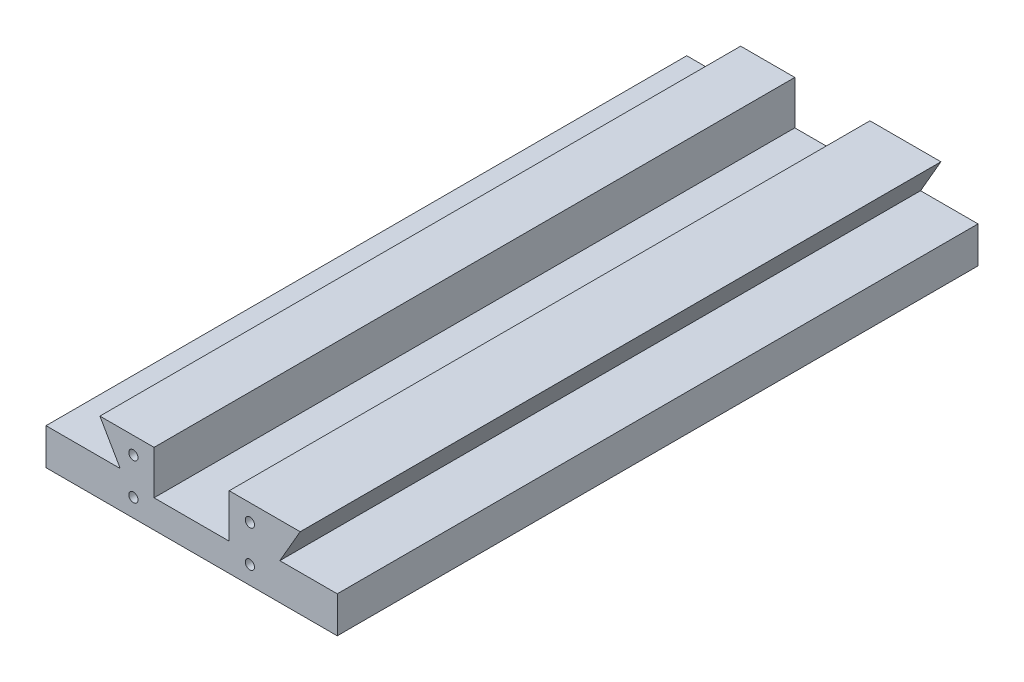
SolidWorks part; units mm, degrees
material "Ductile Iron"
ref_plane "Front Plane" through (0, 0, 0) normal (0, 0, 1) x (1, 0, 0)
ref_plane "Top Plane" through (0, 0, 0) normal (0, 1, 0) x (1, 0, 0)
ref_plane "Right Plane" through (0, 0, 0) normal (1, 0, 0) x (0, 0, -1)
sketch "Sketch6" plane through (0, 0, 0) normal (0, 0, 1) x (1, 0, 0)
  line B0 (-63.5, 0) -> (63.5, 0)
  line B1 (63.5, 0) -> (63.5, 15.875)
  line B2 (63.5, 15.875) -> (38.4596, 15.875)
  line B3 (38.4596, 15.875) -> (47.625, 31.75)
  line B4 (47.625, 31.75) -> (16.0563, 31.75)
  line B5 (-40.2927, 31.75) -> (-31.1272, 15.875)
  line B6 (-31.1272, 15.875) -> (-63.5, 15.875)
  line B7 (-63.5, 15.875) -> (-63.5, 0)
  line B8 (-38.4596, 15.875) -> (-47.625, 31.75)
  line B9 (-47.625, 31.75) -> (-40.2927, 31.75)
  line B10 (-16.0563, 31.75) -> (-16.0563, 12.7) construction
  line B11 (-16.0563, 12.7) -> (16.0563, 12.7) construction
  line B12 (16.0563, 12.7) -> (16.0563, 31.75) construction
  line B13 (-16.0563, 31.75) -> (-40.2927, 31.75)
  line B14 (-63.5, 15.875) -> (-63.5, 47.625)
  line B15 (-63.5, 47.625) -> (63.5, 47.625)
  line B16 (63.5, 47.625) -> (63.5, 15.875)
  line B17 (-16.0563, 31.75) -> (16.0563, 31.75) construction
  line B18 (0, 47.625) -> (0, 0) construction
  line B19 (-38.4596, 15.875) -> (38.4596, 15.875) construction
  line B20 (-28.702, 36.957) -> (28.702, 36.957) construction
  line B21 (-25.4, 7.874) -> (25.4, 7.874) construction
  line B22 (-25.4, 7.874) -> (-25.4, 23.8125) construction
  line B23 (25.4, 7.874) -> (25.4, 23.8125) construction
  line B24 (-52.832, 23.8125) -> (52.832, 23.8125) construction
  circle B25 centre (0, 22.225) radius 18.669 construction
  line B26 (40.2927, 31.75) -> (31.1272, 15.875)
  line B27 (31.1272, 15.875) -> (38.4596, 15.875)
  line B28 (-15.875, 31.75) -> (-15.875, 12.7)
  line B29 (-16.0563, 31.75) -> (-15.875, 31.75)
  line B30 (-15.875, 12.7) -> (15.875, 12.7)
  line B31 (15.875, 12.7) -> (15.875, 31.75)
  line B32 (15.875, 31.75) -> (16.0563, 31.75)
sketch_block_instance "dovetail pair-2"
sketch_block "dovetail pair" parameters "D8"=37.338, "D1"=60, "D2"=127, "D3"=6.35, "D4"=15.875, "D5"=31.75, "D6"=95.25, "D7"=19.05, "D9"=60, "D10"=31.75, "D11"=50.8, "D12"=23.876, "D13"=7.874, "D14"=10.668, "D15"=34.798, "D16"=21.082, "D17"=7.9375, "D18"=24.4437
sketch "dovetail-male-profile" plane through (0, 0, 0) normal (0, 0, 1) x (1, 0, 0)
  line L0 (47.3317, 31.242) -> (16.383, 31.242)
  line L1 (-16.383, 31.242) -> (-39.9994, 31.242)
  line L2 (16.383, 31.242) -> (16.383, 12.192)
  line L3 (16.383, 12.192) -> (-16.383, 12.192)
  line L4 (-16.383, 12.192) -> (-16.383, 31.242)
  line L5 (0, 47.625) -> (0, 0) construction
  line L7 (63.5, 15.875) -> (38.4596, 15.875) construction
  line L8 (63.5, 0) -> (63.5, 15.875) construction
  line L9 (-63.5, 0) -> (63.5, 0) construction
  line L10 (-63.5, 15.875) -> (-63.5, 0) construction
  line L11 (-31.1272, 15.875) -> (-63.5, 15.875) construction
  line L12 (38.4596, 15.875) -> (47.625, 31.75) construction
  line L13 (-31.1272, 15.875) -> (-39.9994, 31.242)
  line L15 (63.5, 15.875) -> (38.4596, 15.875)
  line L16 (63.5, 0) -> (63.5, 15.875)
  line L17 (-63.5, 0) -> (63.5, 0)
  line L18 (-63.5, 15.875) -> (-63.5, 0)
  line L19 (-31.1272, 15.875) -> (-63.5, 15.875)
  line L20 (-40.2927, 31.75) -> (-31.1272, 15.875) construction
  line L21 (38.4596, 15.875) -> (47.3317, 31.242)
  line L23 (47.625, 31.75) -> (16.0563, 31.75) construction
  line L25 (-16.0563, 12.7) -> (16.0563, 12.7) construction
  line L27 (15.875, 12.7) -> (15.875, 31.75) construction
  point P23 (0, 12.192)
  dimension "D2" = 0.508
  dimension "D1" = 0.508
  dimension "D3" = 0.508
extrude "x-guide-extrude" add sketch "dovetail-male-profile" along normal blind 279.4
hole_wizard "end plate holes" positions "Sketch2" profile "Sketch3" tap size "#10-32" standard "ANSI Inch"
sketch "Sketch2" plane through (0, 0, 0) normal (0, 0, -1) x (-1, 0, 0)
  point P27 (-25.4, 23.8125)
  point P29 (25.4, 23.8125)
  point P31 (25.4, 7.874)
  point P33 (-25.4, 7.874)
sketch "Sketch3" plane through (25.4, 23.8125, 0) normal (1, 0, 0) x (0, 1, 0)
  line L0 (0, 0) -> (0, 13.1513)
  line L1 (0, 13.1513) -> (2.0193, 11.938)
  line L2 (2.0193, 11.938) -> (2.0193, 0)
  line L3 (2.0193, 0) -> (0, 0)
  line L4 (0, 13.1513) -> (-2.0193, 11.938) construction
  line L5 (0, -6.35) -> (0, 107.95) construction
  dimension "Tap Drill Dia." = 4.0386
  dimension "Tap Drill Depth" = 11.938
  dimension "Drill Angle" = 118
cosmetic thread "Hole Thread1" parameters "D1"=9.652, "D2"=4.826
cosmetic thread "Hole Thread2" parameters "D1"=9.652, "D2"=4.826
cosmetic thread "Hole Thread9" parameters "D1"=9.652, "D2"=4.826
cosmetic thread "Hole Thread10" parameters "D1"=9.652, "D2"=4.826
hole_wizard "end plate holes 2" positions "Sketch4" profile "Sketch5" tap size "#10-32" standard "ANSI Inch"
sketch "Sketch4" plane through (0, 0, 279.4) normal (0, 0, 1) x (1, 0, 0)
  point P8 (25.4, 23.8125)
  point P10 (25.4, 7.874)
  point P12 (-25.4, 7.874)
  point P14 (-25.4, 23.8125)
cosmetic thread "Hole Thread5" parameters "D1"=9.652, "D2"=4.826
cosmetic thread "Hole Thread6" parameters "D1"=9.652, "D2"=4.826
cosmetic thread "Hole Thread11" parameters "D1"=9.652, "D2"=4.826
cosmetic thread "Hole Thread12" parameters "D1"=9.652, "D2"=4.826
sketch "Sketch5" plane through (25.4, 23.8125, 279.4) normal (1, 0, 0) x (0, -1, 0)
  line L0 (0, 0) -> (0, 13.1513)
  line L1 (0, 13.1513) -> (2.0193, 11.938)
  line L2 (2.0193, 11.938) -> (2.0193, 0)
  line L5 (2.0193, 0) -> (0, 0)
  line L10 (0, 13.1513) -> (-2.0193, 11.938) construction
  line L11 (0, -6.35) -> (0, 107.95) construction
  dimension "Tap Drill Dia." = 4.0386
  dimension "Tap Drill Depth" = 11.938
  dimension "Drill Angle" = 118
equation "\"dovetail-angle\"= 60"
equation "\"dovetail-stock-width\"= 5"
equation "\"dovetail-stock-height\"= 1.25"
equation "\"dovetail-throat-width\"= \"dovetail-stock-width\" - (2 * \"dovetail-depth\")"
equation "\"dovetail-depth\"= 0.5 * \"dovetail-stock-height\""
equation "\"delta-x\"= 6"
equation "\"delta-y\"= 3"
equation "\"gib-thickness\"= 0.25"
equation "\"x-slide-length\"= \"dovetail-stock-width\" + \"delta-x\""
equation "\"y-slide-length\"= \"dovetail-stock-width\" + \"delta-y\""
equation "\"D1@x-guide-extrude\"=\"x-slide-length\""
equation "\"dog-point-diam\"= .149"
equation "\"dog-point-length\"= .067"
equation "\"dovetail-double-height\"= 2 * \"dovetail-depth\" + 0.5"
equation "\"acme-major-diam\"= .5"
equation "\"acme-pitch-diam\"= 0.45"
equation "\"acme-minor-diam\"= 0.4"
equation "\"acme-nut-od\"= 1.47"
equation "\"acme-nut-length\"= 1"
equation "\"acme-nut-trim-height\"= .75"
equation "\"screw-bearing-od\"= 0.5"
equation "\"screw-bearing-length\"= .375"
equation "\"end-plate-thickness\"= \"screw-bearing-length\""
equation "\"screw-bearing-id\"= .3125"
equation "\"screw-add-length\"= 2 * \"end-plate-thickness\" + 1 + 0.5"
equation "\"acme-nut-mount-hole-space-horz\"= 0.95"
equation "\"acme-nut-mount-hole-space-vert\"= 0.5 * \"acme-nut-length\""
equation "\"x-screw-length\"= \"x-slide-length\" + \"screw-add-length\""
equation "\"y-screw-length\"= \"y-slide-length\" + \"screw-add-length\""
equation "\"D2@dovetail pair\"=\"dovetail-stock-width\""
equation "\"D1@dovetail pair\"=\"dovetail-angle\""
equation "\"D3@dovetail pair\"=\"gib-thickness\""
equation "\"D4@dovetail pair\"=\"dovetail-depth\""
equation "\"D5@dovetail pair\"=\"dovetail-stock-height\""
equation "\"D6@dovetail pair\"=\"dovetail-throat-width\""
equation "\"D10@dovetail pair\"=\"dovetail-stock-height\""
equation "\"D7@dovetail pair\"=\"acme-nut-trim-height\""
equation "\"D8@dovetail pair\"=\"acme-nut-od\""
equation "\"D9@dovetail pair\"=\"dovetail-angle\""
equation "\"D17@dovetail pair\"=\"dovetail-depth\"/2"
equation "\"acme-nut-trim-width\"= 1.25"
equation "\"vise-hole-center-dist\"= 6.75"
equation "\"wiper_plate_clearance\"= .03"
equation "\"dial-width\"= 0.5"
equation "\"quarter-twenty-free-fit\"= .2667"
equation "\"acme_nut_clearance\"= .02"
equation "\"dovetail_male_clearance\"= .02"
equation "\"D1@dovetail-male-profile\"=\"dovetail_male_clearance\""
equation "\"D2@dovetail-male-profile\"=\"dovetail_male_clearance\""
equation "\"D3@dovetail-male-profile\"=\"dovetail_male_clearance\""
